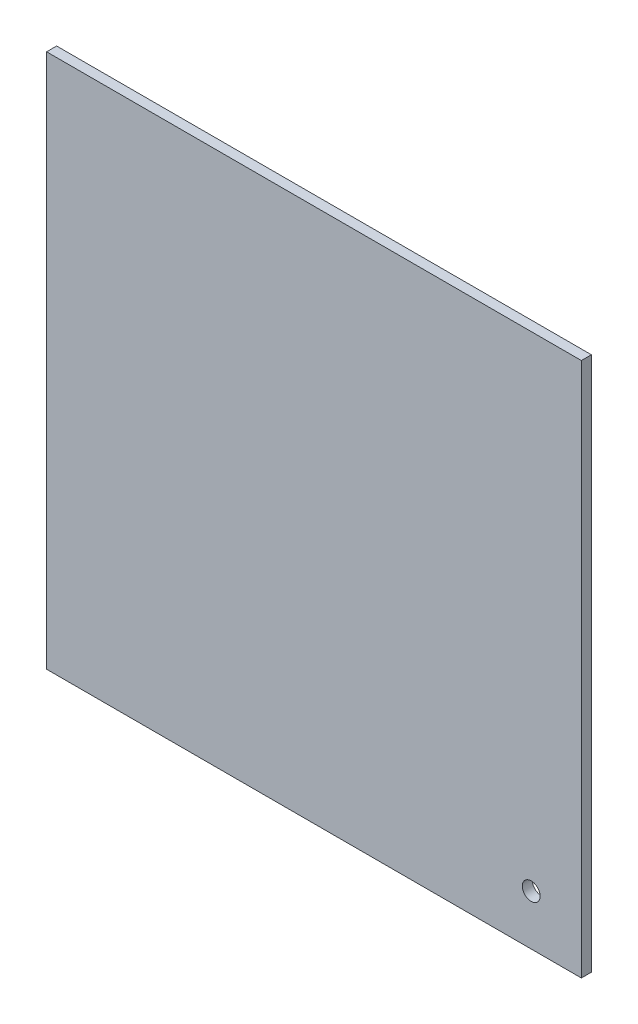
SolidWorks part; units mm, degrees
ref_plane "Front Plane" through (0, 0, 0) normal (0, 0, 1) x (1, 0, 0)
ref_plane "Top Plane" through (0, 0, 0) normal (0, 1, 0) x (1, 0, 0)
ref_plane "Right Plane" through (0, 0, 0) normal (1, 0, 0) x (0, 0, -1)
sketch "Sketch1" plane through (0, 0, 0) normal (0, 0, 1) x (1, 0, 0)
  line L1 (48, -48) -> (-48, -48)
  line L2 (48, -48) -> (48, 48)
  line L3 (48, 48) -> (-48, 48)
  line L4 (-48, -48) -> (-48, 48)
  line L5 (48, -48) -> (-48, 48) construction
  line L6 (48, 48) -> (-48, -48) construction
  point P0 (0, 0)
  dimension "D1" = 96
  dimension "D2" = 96
extrude "Boss-Extrude1" add sketch "Sketch1" along normal blind 1.8
hole_wizard "Ø3.2 (3.2) Diameter Hole1" positions "Sketch5" profile "Sketch4" hole size "Ø3.2" standard "Ansi Metric" end condition up to next
sketch "Sketch5" plane through (0, 0, 1.8) normal (0, 0, 1) x (1, 0, 0)
  line L0 (41.5, -41.5) -> (41.5, -31) construction
  line L1 (31, -41.5) -> (41.5, -41.5) construction
  point P0 (39, -39)
  dimension "D1" = 2.5
  dimension "D2" = 2.5
sketch "Sketch4" plane through (39, -39, 1.8) normal (1, 0, 0) x (0, -1, 0)
  line L0 (0, 0) -> (0, 1.8)
  line L1 (0, 1.8) -> (1.6, 1.8)
  line L2 (1.6, 1.8) -> (1.6, 0)
  line L5 (1.6, 0) -> (0, 0)
  line L11 (0, -6.35) -> (0, 107.95) construction
  dimension "Thru Hole Dia." = 3.2
  dimension "Thru Hole Depth" = 1.8
